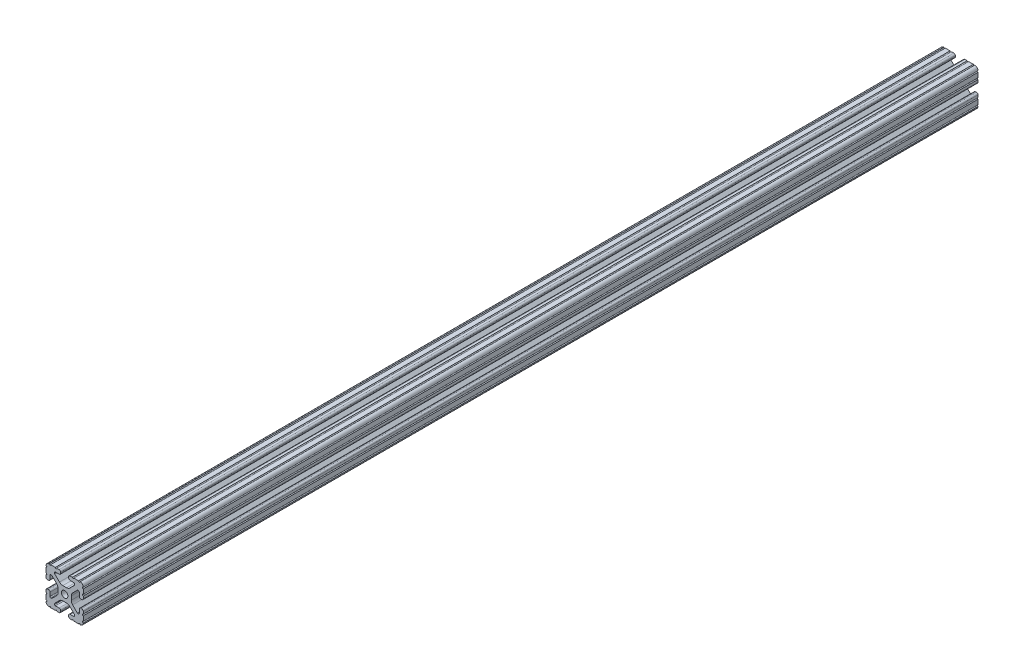
SolidWorks part; units mm, degrees
material "6061 Alloy"
ref_plane "Front Plane" through (0, 0, 0) normal (0, 0, 1) x (1, 0, 0)
ref_plane "Top Plane" through (0, 0, 0) normal (0, 1, 0) x (1, 0, 0)
ref_plane "Right Plane" through (0, 0, 0) normal (1, 0, 0) x (0, 0, -1)
sketch "Sketch1" plane through (0, 0, 0) normal (0, 0, 1) x (1, 0, 0)
  line L0 (0, 25.6181) -> (0, -24.623) construction
  line L1 (-20.8943, 0) -> (20.4607, 0) construction
  line L2 (-10.0229, 12.9148) -> (-5.2522, 8.144)
  line L3 (-10.287, 14.0843) -> (-10.287, 13.5524)
  line L4 (-5.6176, 14.986) -> (-9.3853, 14.986)
  line L5 (-4.064, 17.4964) -> (-4.064, 16.5396)
  line L6 (-7.9742, 19.05) -> (-5.6176, 19.05)
  line L7 (-14.3277, 19.05) -> (-9.4982, 19.05)
  line L8 (-19.05, 9.4961) -> (-19.05, 14.3277)
  line L9 (-19.05, 5.6176) -> (-19.05, 7.9763)
  line L10 (-16.5396, 4.064) -> (-17.4964, 4.064)
  line L11 (-14.986, 9.3853) -> (-14.986, 5.6176)
  line L12 (-13.516, 10.287) -> (-14.0843, 10.287)
  line L13 (-8.1476, 5.2921) -> (-12.8784, 10.0229)
  line L14 (-6.7564, -1.9335) -> (-6.7564, 1.9335)
  line L15 (-12.8784, -10.0229) -> (-8.1476, -5.2921)
  line L16 (-14.0843, -10.287) -> (-13.516, -10.287)
  line L17 (-14.986, -5.6176) -> (-14.986, -9.3853)
  line L18 (-17.4964, -4.064) -> (-16.5396, -4.064)
  line L19 (-19.05, -7.9763) -> (-19.05, -5.6176)
  line L20 (-19.05, -14.3277) -> (-19.05, -9.4961)
  line L21 (-9.4961, -19.05) -> (-14.3277, -19.05)
  line L22 (-5.6176, -19.05) -> (-7.9763, -19.05)
  line L23 (-4.064, -17.4964) -> (-4.064, -16.5396)
  line L24 (10.0229, -12.9148) -> (5.2522, -8.144)
  line L25 (10.287, -14.0843) -> (10.287, -13.5524)
  line L26 (5.6176, -14.986) -> (9.3853, -14.986)
  line L28 (-1.9022, 6.7564) -> (1.9022, 6.7564)
  line L29 (-1.9022, -6.7564) -> (1.9022, -6.7564)
  line L31 (-5.6176, -14.986) -> (-9.3853, -14.986)
  line L32 (-10.287, -14.0843) -> (-10.287, -13.5524)
  line L33 (-10.0229, -12.9148) -> (-5.2522, -8.144)
  line L66 (4.064, -16.5396) -> (4.064, -17.4964)
  line L67 (5.6176, -19.05) -> (7.9763, -19.05)
  line L68 (9.4961, -19.05) -> (14.3277, -19.05)
  line L69 (19.05, -14.3277) -> (19.05, -9.4961)
  line L70 (19.05, -7.9763) -> (19.05, -5.6176)
  line L71 (17.4964, -4.064) -> (16.5396, -4.064)
  line L72 (14.986, -5.6176) -> (14.986, -9.3853)
  line L73 (14.0843, -10.287) -> (13.516, -10.287)
  line L74 (12.8784, -10.0229) -> (8.1476, -5.2921)
  line L75 (6.7564, -1.9335) -> (6.7564, 1.9335)
  line L76 (8.1476, 5.2921) -> (12.8784, 10.0229)
  line L77 (13.516, 10.287) -> (14.0843, 10.287)
  line L78 (14.986, 9.3853) -> (14.986, 5.6176)
  line L79 (16.5396, 4.064) -> (17.4964, 4.064)
  line L80 (19.05, 5.6176) -> (19.05, 7.9763)
  line L81 (19.05, 9.4961) -> (19.05, 14.3277)
  line L82 (14.3277, 19.05) -> (9.4982, 19.05)
  line L83 (7.9742, 19.05) -> (5.6176, 19.05)
  line L84 (4.064, 17.4964) -> (4.064, 16.5396)
  line L85 (5.6176, 14.986) -> (9.3853, 14.986)
  line L86 (10.287, 14.0843) -> (10.287, 13.5524)
  line L87 (10.0229, 12.9148) -> (5.2522, 8.144)
  arc A0 (-10.0229, 12.9148) -> (-10.287, 13.5524) centre (-9.3853, 13.5524) cw
  circle A1 centre (0, 0) radius 3.3274
  arc A2 (-10.287, 14.0843) -> (-9.3853, 14.986) centre (-9.3853, 14.0843) cw
  arc A3 (-4.064, 16.5396) -> (-5.6176, 14.986) centre (-5.6176, 16.5396) cw
  arc A4 (-5.6176, 19.05) -> (-4.064, 17.4964) centre (-5.6176, 17.4964) cw
  arc A5 (-7.9742, 19.05) -> (-9.4982, 19.05) centre (-8.7362, 19.05) cw
  arc A6 (-14.3277, 19.05) -> (-15.8475, 19.05) centre (-15.0876, 18.9933) cw
  arc A7 (-19.05, 15.8475) -> (-15.8475, 19.05) centre (-15.8751, 15.8751) cw
  arc A8 (-19.05, 15.8475) -> (-19.05, 14.3277) centre (-18.9933, 15.0876) cw
  arc A9 (-19.05, 9.4961) -> (-19.05, 7.9763) centre (-18.9933, 8.7362) cw
  arc A10 (-17.4964, 4.064) -> (-19.05, 5.6176) centre (-17.4964, 5.6176) cw
  arc A11 (-14.986, 5.6176) -> (-16.5396, 4.064) centre (-16.5396, 5.6176) cw
  arc A12 (-14.986, 9.3853) -> (-14.0843, 10.287) centre (-14.0843, 9.3853) cw
  arc A13 (-13.516, 10.287) -> (-12.8784, 10.0229) centre (-13.516, 9.3853) cw
  arc A14 (-8.1476, 5.2921) -> (-6.7564, 1.9335) centre (-11.5062, 1.9335) cw
  arc A15 (-6.7564, -1.9335) -> (-8.1476, -5.2921) centre (-11.5062, -1.9335) cw
  arc A16 (-12.8784, -10.0229) -> (-13.516, -10.287) centre (-13.516, -9.3853) cw
  arc A17 (-14.0843, -10.287) -> (-14.986, -9.3853) centre (-14.0843, -9.3853) cw
  arc A18 (-16.5396, -4.064) -> (-14.986, -5.6176) centre (-16.5396, -5.6176) cw
  arc A19 (-19.05, -5.6176) -> (-17.4964, -4.064) centre (-17.4964, -5.6176) cw
  arc A20 (-19.05, -7.9763) -> (-19.05, -9.4961) centre (-18.9933, -8.7362) cw
  arc A21 (-19.05, -14.3277) -> (-19.05, -15.8475) centre (-18.9933, -15.0876) cw
  arc A22 (-15.8475, -19.05) -> (-19.05, -15.8475) centre (-15.8751, -15.8751) cw
  arc A23 (-15.8475, -19.05) -> (-14.3277, -19.05) centre (-15.0876, -18.9933) cw
  arc A24 (-9.4961, -19.05) -> (-7.9763, -19.05) centre (-8.7362, -18.9933) cw
  arc A25 (-4.064, -17.4964) -> (-5.6176, -19.05) centre (-5.6176, -17.4964) cw
  arc A26 (-5.2522, -8.144) -> (-1.9022, -6.7564) centre (-1.9022, -11.494) cw
  arc A27 (1.9022, -6.7564) -> (5.2522, -8.144) centre (1.9022, -11.494) cw
  arc A28 (10.0229, -12.9148) -> (10.287, -13.5524) centre (9.3853, -13.5524) cw
  arc A29 (10.287, -14.0843) -> (9.3853, -14.986) centre (9.3853, -14.0843) cw
  arc A30 (4.064, -16.5396) -> (5.6176, -14.986) centre (5.6176, -16.5396) cw
  arc A31 (-4.064, -16.5396) -> (-5.6176, -14.986) centre (-5.6176, -16.5396) ccw
  arc A32 (-10.287, -14.0843) -> (-9.3853, -14.986) centre (-9.3853, -14.0843) ccw
  arc A33 (-10.0229, -12.9148) -> (-10.287, -13.5524) centre (-9.3853, -13.5524) ccw
  arc A79 (4.064, -17.4964) -> (5.6176, -19.05) centre (5.6176, -17.4964) ccw
  arc A80 (9.4961, -19.05) -> (7.9763, -19.05) centre (8.7362, -18.9933) ccw
  arc A81 (15.8475, -19.05) -> (14.3277, -19.05) centre (15.0876, -18.9933) ccw
  arc A82 (15.8475, -19.05) -> (19.05, -15.8475) centre (15.8751, -15.8751) ccw
  arc A83 (19.05, -14.3277) -> (19.05, -15.8475) centre (18.9933, -15.0876) ccw
  arc A84 (19.05, -7.9763) -> (19.05, -9.4961) centre (18.9933, -8.7362) ccw
  arc A85 (19.05, -5.6176) -> (17.4964, -4.064) centre (17.4964, -5.6176) ccw
  arc A86 (16.5396, -4.064) -> (14.986, -5.6176) centre (16.5396, -5.6176) ccw
  arc A87 (14.0843, -10.287) -> (14.986, -9.3853) centre (14.0843, -9.3853) ccw
  arc A88 (12.8784, -10.0229) -> (13.516, -10.287) centre (13.516, -9.3853) ccw
  arc A89 (6.7564, -1.9335) -> (8.1476, -5.2921) centre (11.5062, -1.9335) ccw
  arc A90 (8.1476, 5.2921) -> (6.7564, 1.9335) centre (11.5062, 1.9335) ccw
  arc A91 (13.516, 10.287) -> (12.8784, 10.0229) centre (13.516, 9.3853) ccw
  arc A92 (14.986, 9.3853) -> (14.0843, 10.287) centre (14.0843, 9.3853) ccw
  arc A93 (14.986, 5.6176) -> (16.5396, 4.064) centre (16.5396, 5.6176) ccw
  arc A94 (17.4964, 4.064) -> (19.05, 5.6176) centre (17.4964, 5.6176) ccw
  arc A95 (19.05, 9.4961) -> (19.05, 7.9763) centre (18.9933, 8.7362) ccw
  arc A96 (19.05, 15.8475) -> (19.05, 14.3277) centre (18.9933, 15.0876) ccw
  arc A97 (19.05, 15.8475) -> (15.8475, 19.05) centre (15.8751, 15.8751) ccw
  arc A98 (14.3277, 19.05) -> (15.8475, 19.05) centre (15.0876, 18.9933) ccw
  arc A99 (7.9742, 19.05) -> (9.4982, 19.05) centre (8.7362, 19.05) ccw
  arc A100 (5.6176, 19.05) -> (4.064, 17.4964) centre (5.6176, 17.4964) ccw
  arc A101 (4.064, 16.5396) -> (5.6176, 14.986) centre (5.6176, 16.5396) ccw
  arc A102 (10.287, 14.0843) -> (9.3853, 14.986) centre (9.3853, 14.0843) ccw
  arc A103 (10.0229, 12.9148) -> (10.287, 13.5524) centre (9.3853, 13.5524) ccw
  arc A104 (1.9022, 6.7564) -> (5.2522, 8.144) centre (1.9022, 11.494) ccw
  arc A105 (-5.2522, 8.144) -> (-1.9022, 6.7564) centre (-1.9022, 11.494) ccw
  dimension "D1" = 6.6548
  dimension "D2" = 19.05
  dimension "D3" = 38.1
  dimension "D4" = 20.574
  dimension "D5" = 13.5128
  dimension "D6" = 4.064
  dimension "D7" = 8.128
  dimension "D8" = 4.064
  dimension "D9" = 12.2936
extrude "Extrude1" add sketch "Sketch1" against normal blind 914.4
